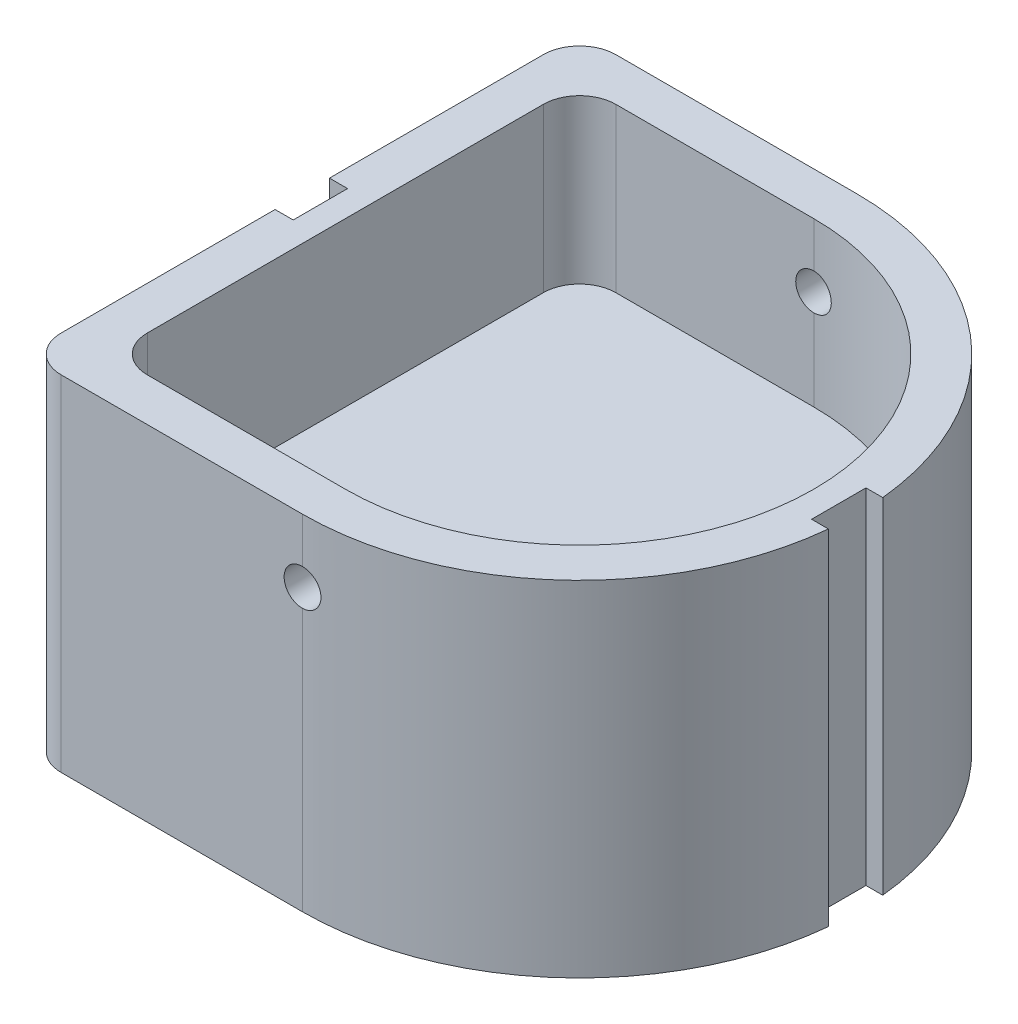
SolidWorks part; units mm, degrees
material "Melamine resin"
ref_plane "Front Plane" through (0, 0, 0) normal (0, 0, 1) x (1, 0, 0)
ref_plane "Top Plane" through (0, 0, 0) normal (0, 1, 0) x (1, 0, 0)
ref_plane "Right Plane" through (0, 0, 0) normal (1, 0, 0) x (0, 0, -1)
sketch "Sketch1" plane through (0, 0, 0) normal (0, 1, 0) x (1, 0, 0)
  line L1 (-13.3, 15.3) -> (0, 15.3)
  line L2 (-15.3, 13.3) -> (-15.3, -13.3)
  line L3 (-13.3, -15.3) -> (0, -15.3)
  line L5 (-15.3, 15.3) -> (15.3, -15.3) construction
  line L6 (-15.3, -15.3) -> (15.3, 15.3) construction
  arc A2 (-13.3, -15.3) -> (-15.3, -13.3) centre (-13.3, -13.3) cw
  arc A3 (-15.3, 13.3) -> (-13.3, 15.3) centre (-13.3, 13.3) cw
  arc A4 (0, 15.3) -> (0, -15.3) centre (0, 0) cw
  point P0 (0, 0)
  dimension "D3" = 15.3
  dimension "D4" = 13.3
  dimension "D1" = 30.6
  dimension "D2" = 30.6
  dimension "D5" = 13.3
extrude "Boss-Extrude1" add sketch "Sketch1" along normal blind 19
sketch "Sketch2" plane through (0, 19, 0) normal (0, 1, 0) x (1, 0, 0)
  line L1 (-10.925, 12.925) -> (0, 12.925)
  line L2 (-12.925, 10.925) -> (-12.925, -10.925)
  line L3 (-10.925, -12.925) -> (0, -12.925)
  line L5 (-12.925, 12.925) -> (12.925, -12.925) construction
  line L6 (-12.925, -12.925) -> (12.925, 12.925) construction
  arc A0 (-12.925, 10.925) -> (-10.925, 12.925) centre (-10.925, 10.925) cw
  arc A1 (-10.925, -12.925) -> (-12.925, -10.925) centre (-10.925, -10.925) cw
  arc A4 (0, 12.925) -> (0, -12.925) centre (0, 0) cw
  point P0 (0, 0)
  dimension "D3" = 2
  dimension "D4" = 2
  dimension "D5" = 12.925
  dimension "D1" = 25.85
  dimension "D2" = 25.85
extrude "Cut-Extrude1" cut sketch "Sketch2" against normal blind 9
sketch "Sketch3" plane through (0, 0, 0) normal (0, 0, 1) x (1, 0, 0)
  line L3 (-13.3, 19) -> (0, 19) construction
  circle A0 centre (0, 15.5) radius 1
  point P11 (0, 0)
  dimension "D1" = 2
  dimension "D3" = 3.5
extrude "Cut-Extrude2" cut sketch "Sketch3" against normal through all both and the other way through all
sketch "Sketch8" plane through (0, 0, 0) normal (0, 1, 0) x (1, 0, 0)
  line L0 (0, 15.3) -> (-13.3, 15.3) construction
  line L7 (-15.3, 13.3) -> (-15.3, -13.3) construction
  line L8 (0, 18.536) -> (0, -20.9321) construction
  line L10 (14.3, -1.5) -> (15.3, -1.5)
  line L11 (14.3, -1.5) -> (14.3, 1.5)
  line L12 (14.3, 1.5) -> (15.3, 1.5)
  line L13 (15.3, -1.5) -> (15.3, 1.5)
  line L14 (14.3, -1.5) -> (15.3, 1.5) construction
  line L15 (14.3, 1.5) -> (15.3, -1.5) construction
  line L22 (-14.3, -1.5) -> (-15.3, -1.5)
  line L23 (-14.3, -1.5) -> (-14.3, 1.5)
  line L24 (-14.3, 1.5) -> (-15.3, 1.5)
  line L25 (-15.3, -1.5) -> (-15.3, 1.5)
  line L26 (-14.3, -1.5) -> (-15.3, 1.5) construction
  line L27 (-14.3, 1.5) -> (-15.3, -1.5) construction
  point P2 (0, 0)
  point P3 (0, 0)
  point P6 (14.8, 0)
  point P14 (0, 0)
  point P15 (0, 0)
  dimension "D1" = 3
  dimension "D2" = 1
  dimension "D3" = 3
  dimension "D4" = 1
  dimension "D5" = 13.8
  dimension "D6" = 13.8
extrude "Cut-Extrude9" cut sketch "Sketch8" along normal through all
